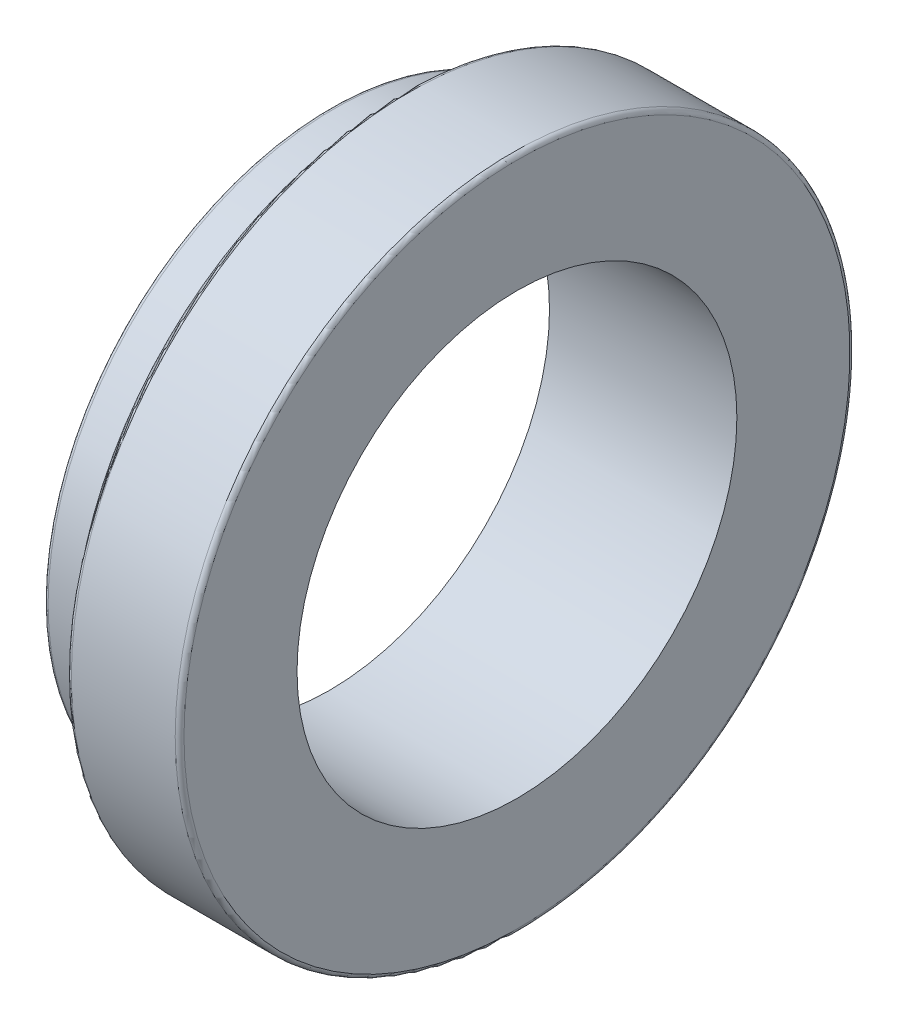
SolidWorks part; units mm, degrees
material "CD4Mc-U Duplex Stainless Steel"
ref_plane "Front Plane" through (0, 0, 0) normal (0, 0, 1) x (1, 0, 0)
ref_plane "Top Plane" through (0, 0, 0) normal (0, 1, 0) x (1, 0, 0)
ref_plane "Right Plane" through (0, 0, 0) normal (1, 0, 0) x (0, 0, -1)
sketch "Sketch1" plane through (0, 0, 0) normal (0, 0, 1) x (1, 0, 0)
  line L0 (0, 0) -> (79.6085, 0) construction
  line L3 (1.7959, 31.75) -> (1.7959, 40.64)
  line L4 (2.4309, 41.275) -> (10.6859, 41.275)
  line L6 (10.9399, 46.0375) -> (12.3247, 46.0375)
  line L7 (12.5787, 46.2915) -> (12.5787, 48.0695)
  line L8 (13.2137, 48.7045) -> (28.2119, 48.7045)
  line L9 (28.8469, 48.0695) -> (28.8469, 31.75)
  line L10 (28.8469, 31.75) -> (1.7959, 31.75)
  line L11 (10.6859, 45.7835) -> (10.6859, 41.275)
  arc A2 (12.5787, 48.0695) -> (13.2137, 48.7045) centre (13.2137, 48.0695) cw
  arc A3 (28.2119, 48.7045) -> (28.8469, 48.0695) centre (28.2119, 48.0695) cw
  arc A5 (1.7959, 40.64) -> (2.4309, 41.275) centre (2.4309, 40.64) cw
  arc A7 (12.3247, 46.0375) -> (12.5787, 46.2915) centre (12.3247, 46.2915) ccw
  arc A8 (10.9399, 46.0375) -> (10.6859, 45.7835) centre (10.9399, 45.7835) ccw
  point P4 (1.7959, 31.75)
  point P6 (1.7959, 31.9539)
  dimension "D5" = 46.0375
  dimension "D7" = 0.254
  dimension "D1" = 48.7045
  dimension "D2" = 8.89
  dimension "D3" = 18.161
  dimension "D4" = 41.275
  dimension "D6" = 31.75
revolve "Revolve1" add sketch "Sketch1" angle 360 about L0
